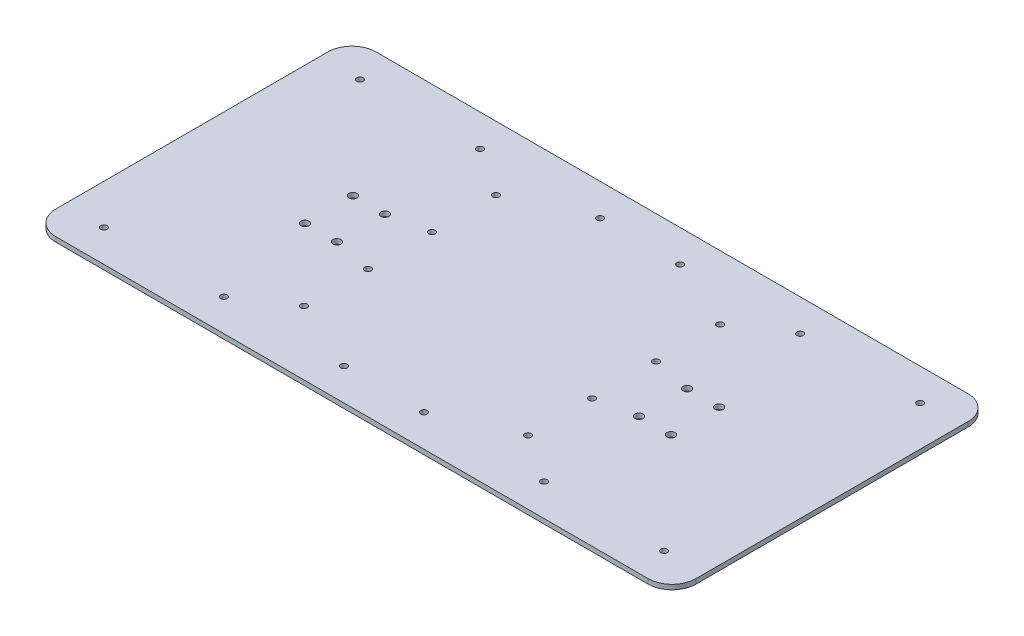
SolidWorks part; units mm, degrees
ref_plane "前视基准面" through (0, 0, 0) normal (0, 0, 1) x (1, 0, 0)
ref_plane "上视基准面" through (0, 0, 0) normal (0, 1, 0) x (1, 0, 0)
ref_plane "右视基准面" through (0, 0, 0) normal (1, 0, 0) x (0, 0, -1)
sketch "草图2" plane through (0, 0, 0) normal (0, 1, 0) x (1, 0, 0)
  line L1 (-185, 100) -> (185, 100)
  line L2 (-200, 85) -> (-200, -85)
  line L3 (-185, -100) -> (185, -100)
  line L4 (200, 85) -> (200, -85)
  line L5 (-200, 100) -> (200, -100) construction
  line L6 (-200, -100) -> (200, 100) construction
  arc A0 (-185, 100) -> (-200, 85) centre (-185, 85) ccw
  arc A1 (185, -100) -> (200, -85) centre (185, -85) ccw
  arc A2 (200, 85) -> (185, 100) centre (185, 85) ccw
  arc A3 (-185, -100) -> (-200, -85) centre (-185, -85) cw
  point P0 (0, 0)
  dimension "D1" = 15
extrude "凸台-拉伸2" add sketch "草图2" along normal blind 3
sketch "草图3" plane through (0, 3, 0) normal (0, 1, 0) x (1, 0, 0)
  circle A0 centre (-114.4, 15) radius 2.5
  circle A1 centre (-94.4, 15) radius 2.5
  circle A2 centre (-114.4, -15) radius 2.5
  circle A3 centre (-94.4, -15) radius 2.5
  circle A5 centre (94.4, 15) radius 2.5
  circle A6 centre (114.4, 15) radius 2.5
  circle A7 centre (114.4, -15) radius 2.5
  circle A8 centre (94.4, -15) radius 2.5
extrude "切除-拉伸1" cut sketch "草图3" against normal blind 3
sketch "草图4" plane through (0, 3, 0) normal (0, 1, 0) x (1, 0, 0)
  circle A0 centre (-175, 80) radius 2
  circle A1 centre (-100, 80) radius 2
  circle A2 centre (-25, 80) radius 2
  circle A3 centre (175, 80) radius 2
  circle A5 centre (100, 80) radius 2
  circle A6 centre (25, 80) radius 2
  dimension "D1" = 3
  dimension "D2" = 3
extrude "切除-拉伸2" cut sketch "草图4" against normal through all
sketch "草图5" plane through (0, 3, 0) normal (0, 1, 0) x (1, 0, 0)
  circle A3 centre (-175, -80) radius 2
  circle A4 centre (-100, -80) radius 2
  circle A5 centre (-25, -80) radius 2
  circle A6 centre (25, -80) radius 2
  circle A7 centre (100, -80) radius 2
  circle A8 centre (175, -80) radius 2
  dimension "D1" = 3
  dimension "D2" = 3
extrude "切除-拉伸3" cut sketch "草图5" against normal through all
sketch "草图6" plane through (0, 3, 0) normal (0, 1, 0) x (1, 0, 0)
  circle A0 centre (-70, 60) radius 2
  circle A1 centre (-70, 20) radius 2
  circle A2 centre (-70, -20) radius 2
  circle A3 centre (-70, -60) radius 2
  dimension "D1" = 4
extrude "切除-拉伸4" cut sketch "草图6" against normal through all
sketch "草图8" plane through (0, 3, 0) normal (0, 1, 0) x (1, 0, 0)
  circle A0 centre (70, 60) radius 2
  circle A2 centre (70, 20) radius 2
  circle A3 centre (70, -20) radius 2
  circle A4 centre (70, -60) radius 2
  dimension "D1" = 4
extrude "切除-拉伸6" cut sketch "草图8" against normal through all
